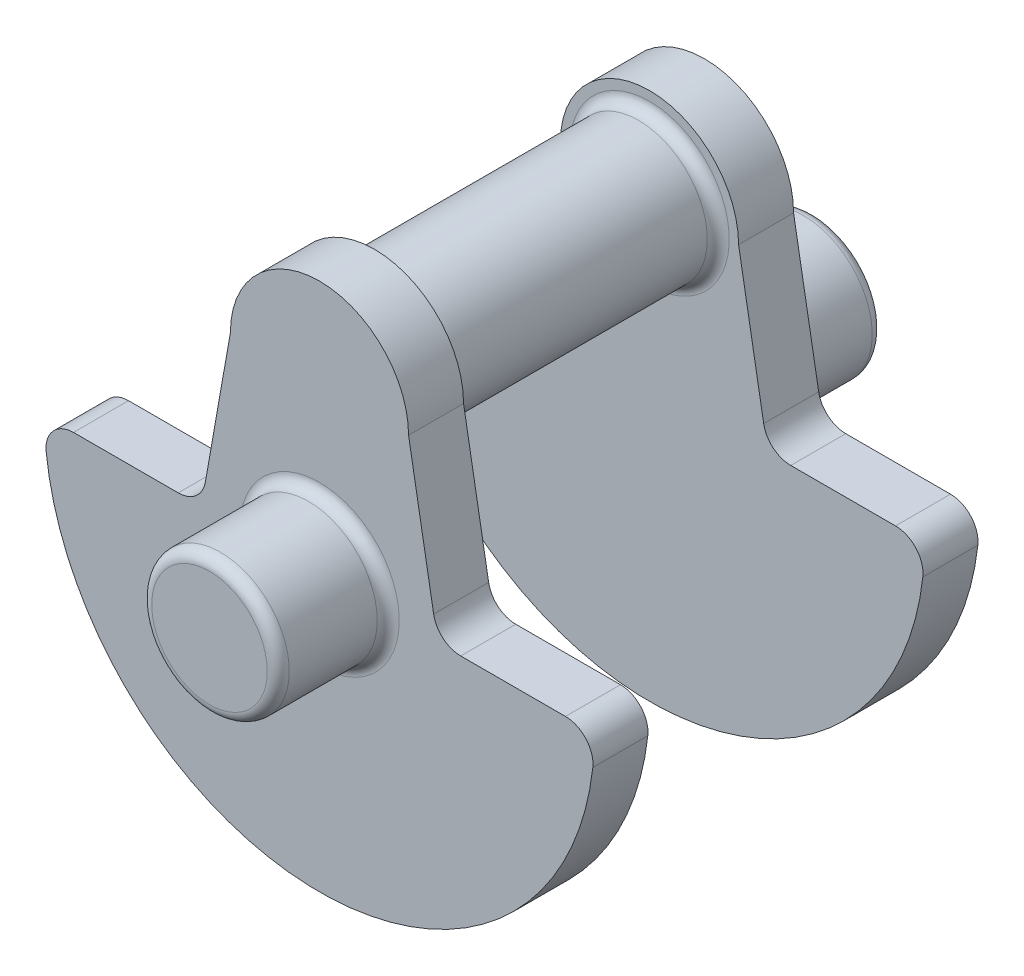
SolidWorks part; units mm, degrees
material "Plain Carbon Steel"
ref_plane "Front Plane" through (0, 0, 0) normal (0, 0, 1) x (1, 0, 0)
ref_plane "Top Plane" through (0, 0, 0) normal (0, 1, 0) x (1, 0, 0)
ref_plane "Right Plane" through (0, 0, 0) normal (1, 0, 0) x (0, 0, -1)
sketch "Sketch1" plane through (0, 0, 0) normal (0, 0, 1) x (1, 0, 0)
  line L0 (0, 0) -> (0, -30) construction
  line L1 (-50, -30) -> (-21.484, -30)
  line L2 (21.484, -30) -> (50, -30)
  line L3 (-16.1942, 0) -> (-21.484, -30)
  line L4 (16.1942, 0) -> (21.484, -30)
  arc A0 (16.1942, 0) -> (-16.1942, 0) centre (0, 0) ccw
  arc A1 (-50, -30) -> (50, -30) centre (0, -30) ccw
  dimension "D1" = 30
  dimension "D2" = 10
extrude "Boss-Extrude1" add sketch "Sketch1" along normal mid plane 10
sketch "Sketch2" plane through (0, 0, 5) normal (0, 0, 1) x (1, 0, 0)
  circle A0 centre (0, -30) radius 12.5
  dimension "D1" = 25
  dimension "D2" = 30
extrude "Boss-Extrude2" add sketch "Sketch2" along normal blind 20
sketch "Sketch3" plane through (0, 0, -5) normal (0, 0, -1) x (-1, 0, 0)
  circle A0 centre (0, 0) radius 12.5
  dimension "D1" = 25
extrude "Boss-Extrude3" add sketch "Sketch3" along normal blind 50
ref_plane "Plane1" through (0, 0, -30) normal (0, 0, -1) x (-1, 0, 0)
mirror "Mirror1" about plane through (0, 0, -30) normal (0, 0, -1) of "Boss-Extrude1", "Boss-Extrude2"
fillet "Fillet2" radius 5 8 edges at (-21.484, -30, -60) (-50, -30, -60) (-50, -30, 0) (-21.484, -30, 0) (21.484, -30, -60) (50, -30, -60) (50, -30, 0) (21.484, -30, 0)
fillet "Fillet3" radius 2 6 edges at (12.5, 0, -5) (-12.5, 0, -55) (12.5, -30, -85) (-12.5, -30, -65) (12.5, -30, 25) (12.5, -30, 5)
